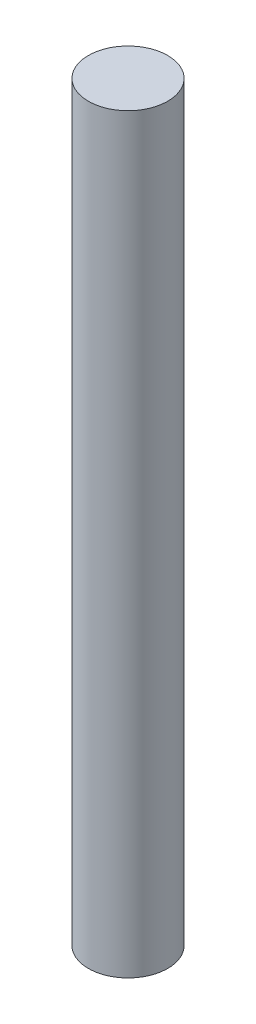
SolidWorks part; units mm, degrees
ref_plane "Front Plane" through (0, 0, 0) normal (0, 0, 1) x (1, 0, 0)
ref_plane "Top Plane" through (0, 0, 0) normal (0, 1, 0) x (1, 0, 0)
ref_plane "Right Plane" through (0, 0, 0) normal (1, 0, 0) x (0, 0, -1)
sketch "Sketch1" plane through (0, 0, 0) normal (0, 1, 0) x (1, 0, 0)
  circle A0 centre (0, 0) radius 1.1938
  dimension "D1" = 2.3876
extrude "Boss-Extrude1" add sketch "Sketch1" along normal blind 22.606
